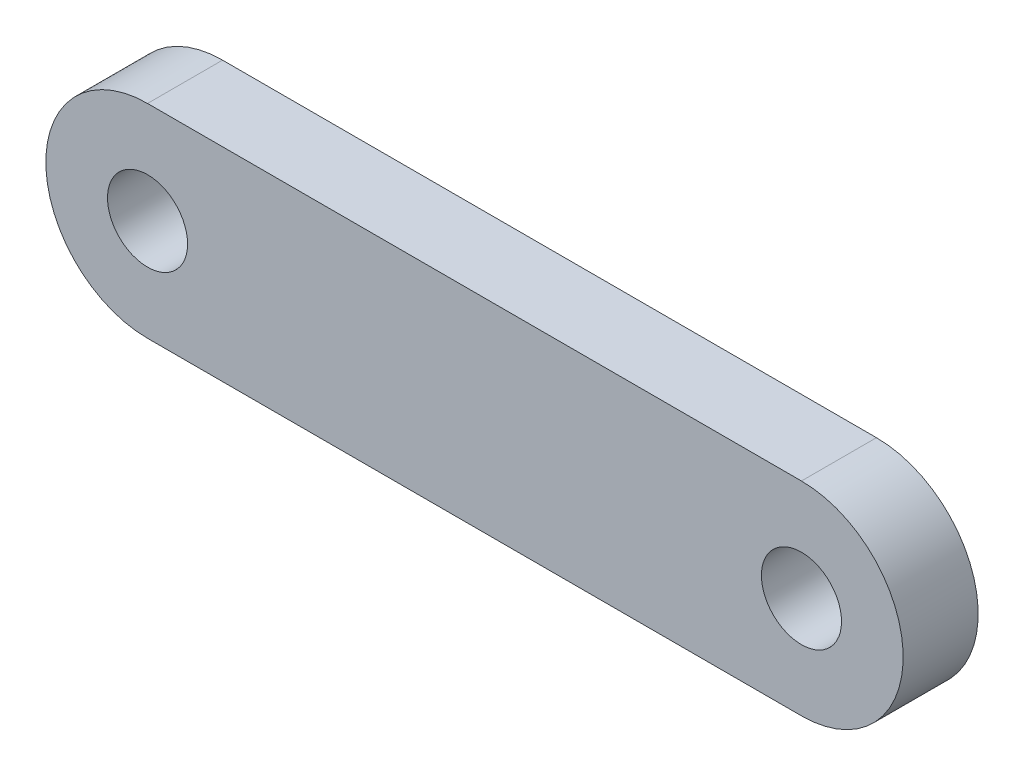
SolidWorks part; units mm, degrees
ref_plane "Front Plane" through (0, 0, 0) normal (0, 0, 1) x (1, 0, 0)
ref_plane "Top Plane" through (0, 0, 0) normal (0, 1, 0) x (1, 0, 0)
ref_plane "Right Plane" through (0, 0, 0) normal (1, 0, 0) x (0, 0, -1)
sketch "Sketch1" plane through (0, 0, 0) normal (0, 0, 1) x (1, 0, 0)
  line L0 (25.7175, 0) -> (-25.7175, 0) construction
  line L1 (25.7175, -8) -> (-25.7175, -8)
  line L2 (25.7175, 8) -> (-25.7175, 8)
  arc A0 (25.7175, -8) -> (25.7175, 8) centre (25.7175, 0) ccw
  arc A1 (-25.7175, 8) -> (-25.7175, -8) centre (-25.7175, 0) ccw
  circle A2 centre (25.7175, 0) radius 3.15
  circle A3 centre (-25.7175, 0) radius 3.15
  point P2 (0, 0)
  dimension "D3" = 6.3
  dimension "D1" = 16
  dimension "D2" = 51.435
extrude "Boss-Extrude1" add sketch "Sketch1" along normal blind 5.9
